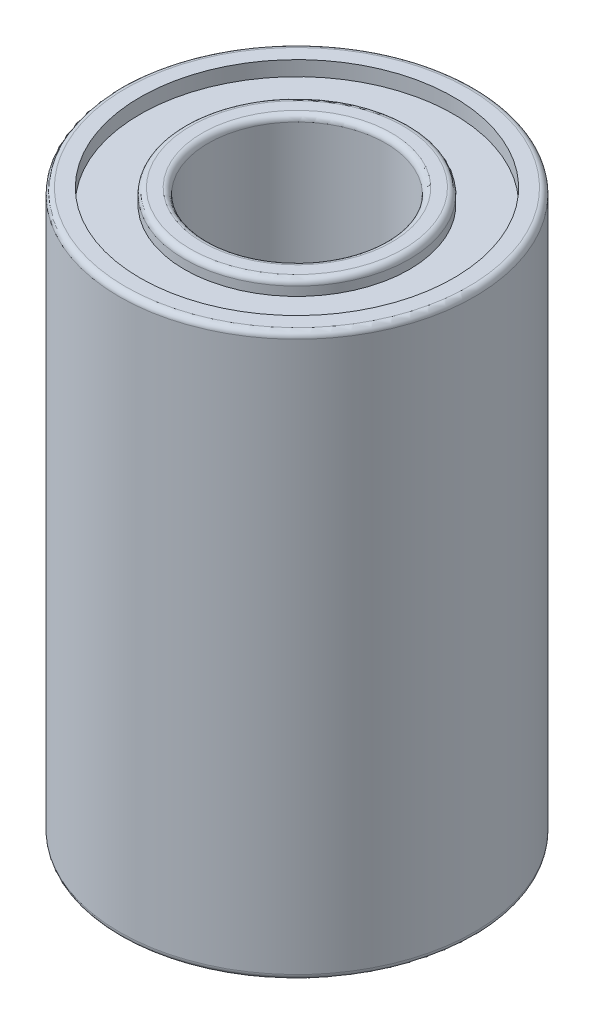
SolidWorks part; units mm, degrees
ref_plane "Front Plane" through (0, 0, 0) normal (0, 0, 1) x (1, 0, 0)
ref_plane "Top Plane" through (0, 0, 0) normal (0, 1, 0) x (1, 0, 0)
ref_plane "Right Plane" through (0, 0, 0) normal (1, 0, 0) x (0, 0, -1)
sketch "Sketch1" plane through (0, 0, 0) normal (0, 1, 0) x (1, 0, 0)
  circle A0 centre (0, 0) radius 6
  circle A1 centre (0, 0) radius 3
  dimension "D1" = 12
  dimension "D2" = 6
extrude "Boss-Extrude1" add sketch "Sketch1" along normal blind 19
sketch "Sketch2" plane through (0, 19, 0) normal (0, 1, 0) x (1, 0, 0)
  circle A0 centre (0, 0) radius 3 construction
  circle A1 centre (0, 0) radius 3
  circle A2 centre (0, 0) radius 3.8
  circle A3 centre (0, 0) radius 5.3
  dimension "D1" = 0.8
  dimension "D2" = 1.5
extrude "Cut-Extrude1" cut sketch "Sketch2" against normal blind 0.5 contours A3 A2
sketch "Sketch3" plane through (0, 0, 0) normal (0, -1, 0) x (1, 0, 0)
  circle A0 centre (0, 0) radius 3.8 construction
  circle A1 centre (0, 0) radius 5.3
  circle A2 centre (0, 0) radius 5.3
  circle A3 centre (0, 0) radius 3.8
  dimension "D1" = 0
extrude "Cut-Extrude2" cut sketch "Sketch3" against normal blind 0.5
fillet "Fillet1" radius 0.2 7 edges at (0, 19, 6) (0, 0, 3) (0, 0, -3.8) (0, 0, -5.3) (0, 0, 6) (0, 19, 3) (0, 19, 3.8)
